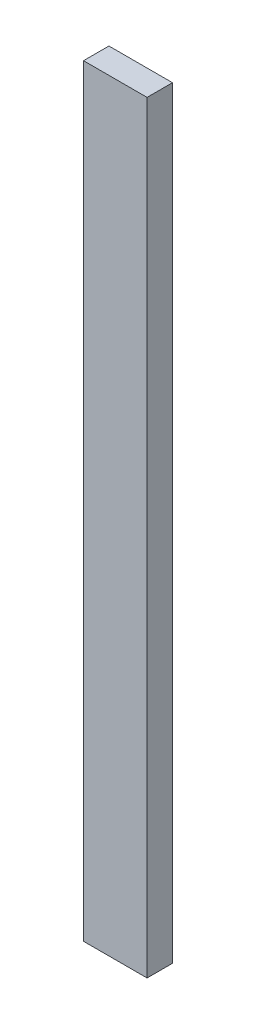
SolidWorks part; units mm, degrees
ref_plane "Front Plane" through (0, 0, 0) normal (0, 0, 1) x (1, 0, 0)
ref_plane "Top Plane" through (0, 0, 0) normal (0, 1, 0) x (1, 0, 0)
ref_plane "Right Plane" through (0, 0, 0) normal (1, 0, 0) x (0, 0, -1)
sketch "Sketch1" plane through (0, 0, 0) normal (0, 1, 0) x (1, 0, 0)
  line L1 (25, -10) -> (-25, -10)
  line L2 (25, -10) -> (25, 10)
  line L3 (25, 10) -> (-25, 10)
  line L4 (-25, -10) -> (-25, 10)
  line L5 (25, -10) -> (-25, 10) construction
  line L6 (25, 10) -> (-25, -10) construction
  point P0 (0, 0)
  dimension "D1" = 50
  dimension "D2" = 20
extrude "Boss-Extrude1" add sketch "Sketch1" along normal mid plane 600
